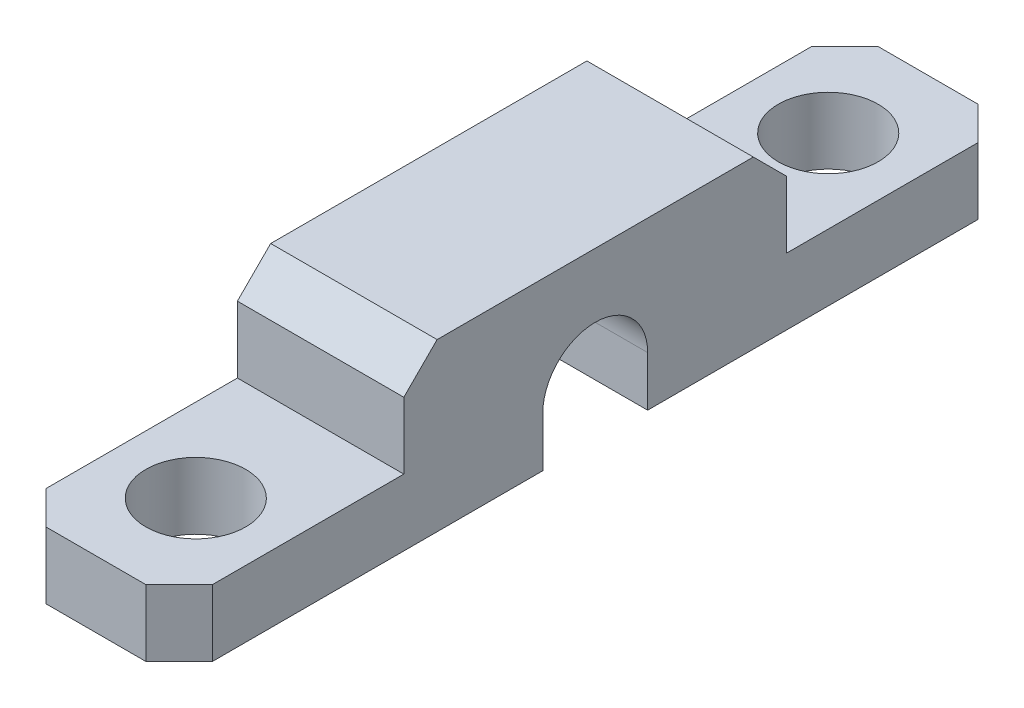
SolidWorks part; units mm, degrees
material "ABS"
ref_plane "Front Plane" through (0, 0, 0) normal (0, 0, 1) x (1, 0, 0)
ref_plane "Top Plane" through (0, 0, 0) normal (0, 1, 0) x (1, 0, 0)
ref_plane "Right Plane" through (0, 0, 0) normal (1, 0, 0) x (0, 0, -1)
sketch "Sketch1" plane through (0, 0, 0) normal (1, 0, 0) x (0, 0, -1)
  line L1 (-25, 5) -> (25, 5)
  line L2 (-25, 5) -> (-25, -5)
  line L3 (-25, -5) -> (25, -5)
  line L4 (25, 5) -> (25, -5)
  line L5 (-25, 5) -> (25, -5) construction
  line L6 (-25, -5) -> (25, 5) construction
  point P0 (0, 0)
  dimension "D1" = 50
  dimension "D2" = 10
extrude "Boss-Extrude1" add sketch "Sketch1" along normal blind 10
sketch "Sketch3" plane through (0, 5, 0) normal (0, 1, 0) x (1, 0, 0)
  line L0 (5, 17.5) -> (5, -17.5) construction
  line L1 (0, 25) -> (10, -25) construction
  line L3 (-7.0651, -11.5) -> (23.7365, -11.5)
  line L4 (-7.0651, -11.5) -> (-7.0651, -29.8854)
  line L5 (-7.0651, -29.8854) -> (23.7365, -29.8854)
  line L6 (23.7365, -11.5) -> (23.7365, -29.8854)
  line L7 (23.7365, 11.5) -> (-10.7262, 11.5)
  line L8 (23.7365, 11.5) -> (23.7365, 30.9997)
  line L9 (23.7365, 30.9997) -> (-10.7262, 30.9997)
  line L10 (-10.7262, 11.5) -> (-10.7262, 30.9997)
  circle A0 centre (5, -17.5) radius 6
  circle A1 centre (5, 17.5) radius 6
  point P6 (5, 0)
  dimension "D1" = 12
  dimension "D2" = 35
extrude "Cut-Extrude1" cut sketch "Sketch3" against normal blind 6 contours L3 L6 L5 L4 | L7 L10 L9 L8 | A1
sketch "Sketch4" plane through (0, -1, 0) normal (0, 1, 0) x (1, 0, 0)
  line L0 (0, 0) -> (10, 0) construction
  line L1 (10, 11.5) -> (10, -11.5) construction
  line L2 (5, 19) -> (5, -19) construction
  circle A0 centre (5, 19) radius 3
  circle A1 centre (5, -19) radius 3
  point P11 (5, 0)
  dimension "D1" = 6
  dimension "D2" = 38
extrude "Cut-Extrude2" cut sketch "Sketch4" against normal blind 6
sketch "Sketch5" plane through (10, 0, 0) normal (1, 0, 0) x (0, 0, -1)
  line L0 (0, 0) -> (0, -2) construction
  line L7 (-3.15, -2) -> (3.15, -2)
  line L8 (-3.15, -2) -> (-3.15, -9.4809)
  line L9 (-3.15, -9.4809) -> (3.15, -9.4809)
  line L10 (3.15, -2) -> (3.15, -9.4809)
  circle A1 centre (0, -2) radius 3.15
  point P0 (0.3673, -2.1349)
  dimension "D2" = 6.3
  dimension "D3" = 2
extrude "Cut-Extrude3" cut sketch "Sketch5" against normal through all
chamfer "Chamfer1" distance 2 angle 45 6 edges at (0, -3, 25) (10, -3, 25) (0, -3, -25) (10, -3, -25) (5, 5, -11.5) (5, 5, 11.5)
